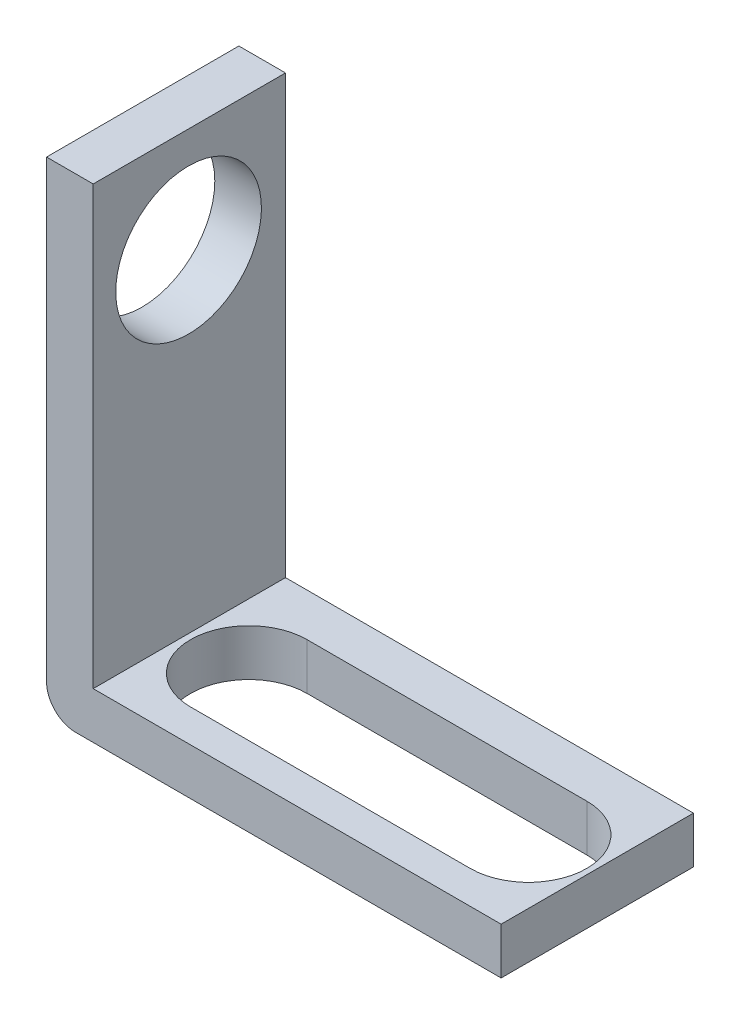
SolidWorks part; units mm, degrees
ref_plane "Front Plane" through (0, 0, 0) normal (0, 0, 1) x (1, 0, 0)
ref_plane "Top Plane" through (0, 0, 0) normal (0, 1, 0) x (1, 0, 0)
ref_plane "Right Plane" through (0, 0, 0) normal (1, 0, 0) x (0, 0, -1)
sketch "Sketch1" plane through (0, 0, 0) normal (0, 0, 1) x (1, 0, 0)
  line L0 (0, 0) -> (0, 75)
  line L1 (0, 75) -> (8, 75)
  line L2 (8, 75) -> (8, 0)
  line L3 (0, 0) -> (0, -3)
  line L4 (5, -8) -> (78, -8)
  line L5 (78, -8) -> (78, 0)
  line L6 (78, 0) -> (8, 0)
  arc A0 (0, -3) -> (5, -8) centre (5, -3) ccw
  point P10 (0, -8)
  dimension "D5" = 5
  dimension "D1" = 75
  dimension "D2" = 8
  dimension "D3" = 8
  dimension "D4" = 78
  dimension "D6" = 75
extrude "Boss-Extrude1" add sketch "Sketch1" along normal blind 33
sketch "Sketch2" plane through (8, 0, 0) normal (1, 0, 0) x (0, 0, -1)
  circle A0 centre (-16.6297, 57) radius 12.5
  dimension "D1" = 25
extrude "Cut-Extrude2" cut sketch "Sketch2" against normal blind 33
sketch "Sketch3" plane through (0, 0, 0) normal (0, 1, 0) x (1, 0, 0)
  line L3 (19.0673, -7.3665) -> (67.0673, -7.3665)
  line L5 (19.0673, -27.3665) -> (67.0673, -27.3665)
  line L7 (19.0673, -7.3665) -> (67.0673, -27.3665) construction
  line L8 (19.0673, -27.3665) -> (67.0673, -7.3665) construction
  arc A0 (19.0673, -7.3665) -> (19.0673, -27.3665) centre (19.0673, -17.3665) ccw
  arc A1 (67.0673, -27.3665) -> (67.0673, -7.3665) centre (67.0673, -17.3665) ccw
  dimension "D4" = 10
  dimension "D5" = 10
  dimension "D2" = 20
  dimension "D3" = 48
extrude "Cut-Extrude10" cut sketch "Sketch3" against normal blind 33
